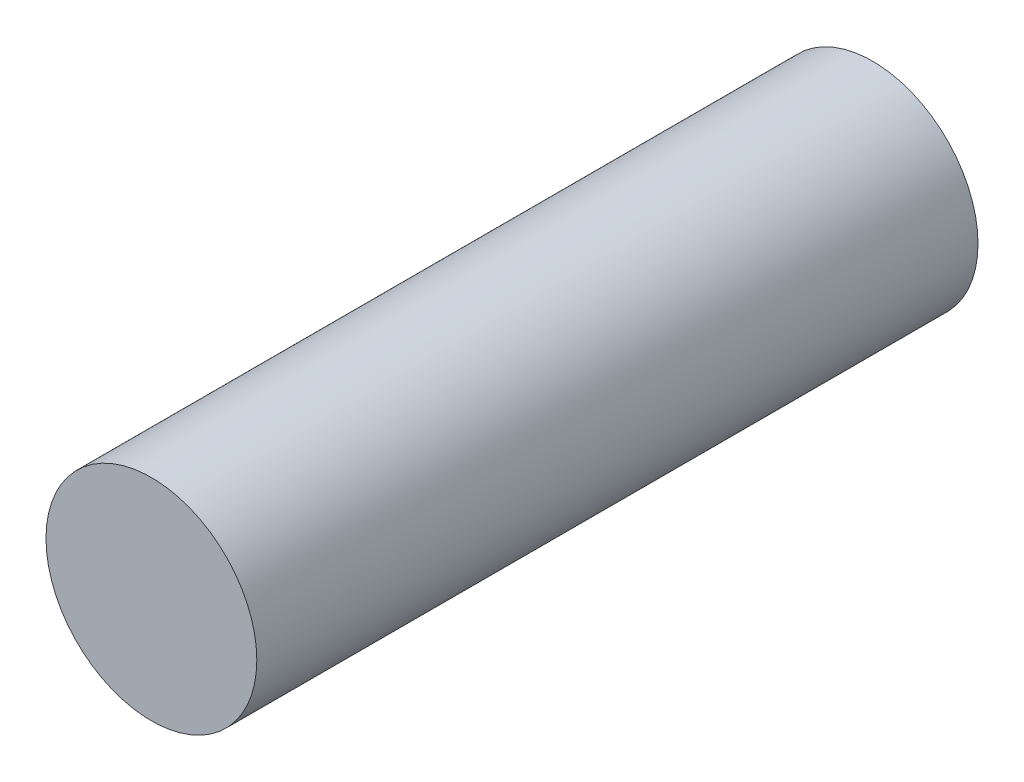
SolidWorks part; units mm, degrees
ref_plane "Front Plane" through (0, 0, 0) normal (0, 0, 1) x (1, 0, 0)
ref_plane "Top Plane" through (0, 0, 0) normal (0, 1, 0) x (1, 0, 0)
ref_plane "Right Plane" through (0, 0, 0) normal (1, 0, 0) x (0, 0, -1)
sketch "Sketch1" plane through (0, 0, 0) normal (0, 0, 1) x (1, 0, 0)
  circle A0 centre (0, 0) radius 9.5
  dimension "D1" = 19
extrude "Boss-Extrude1" add sketch "Sketch1" along normal blind 65
